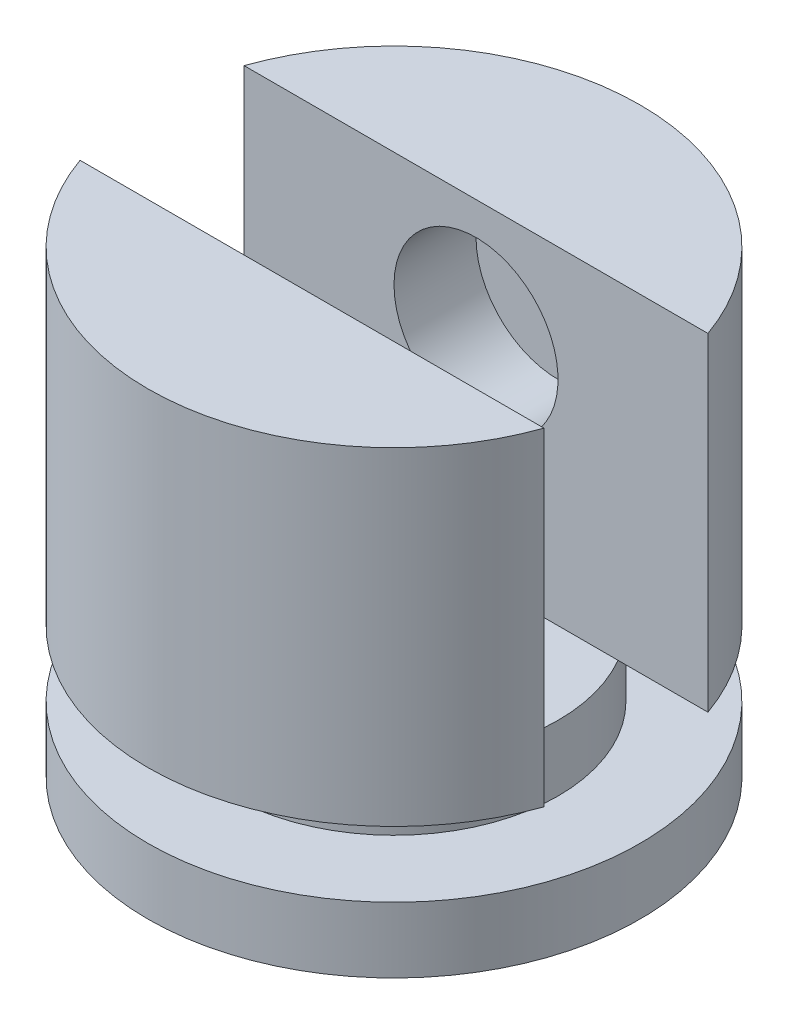
SolidWorks part; units mm, degrees
ref_plane "Front Plane" through (0, 0, 0) normal (0, 0, 1) x (1, 0, 0)
ref_plane "Top Plane" through (0, 0, 0) normal (0, 1, 0) x (1, 0, 0)
ref_plane "Right Plane" through (0, 0, 0) normal (1, 0, 0) x (0, 0, -1)
sketch "Sketch1" plane through (0, 0, 0) normal (0, 1, 0) x (1, 0, 0)
  circle A0 centre (0, 0) radius 10
  dimension "D1" = 20
extrude "Boss-Extrude1" add sketch "Sketch1" against normal blind 4
sketch "Sketch2" plane through (0, -4, 0) normal (0, -1, 0) x (1, 0, 0)
  circle A0 centre (0, 0) radius 15
  dimension "D1" = 30
extrude "Boss-Extrude2" add sketch "Sketch2" along normal blind 4
sketch "Sketch3" plane through (0, 0, 0) normal (0, 1, 0) x (1, 0, 0)
  circle A0 centre (0, 0) radius 15
  dimension "D1" = 30
extrude "Boss-Extrude3" add sketch "Sketch3" along normal blind 20
sketch "Sketch6" plane through (0, 0, 0) normal (0, 1, 0) x (1, 0, 0)
  line L1 (15, 0) -> (-15, 0)
  line L2 (15, 0) -> (15, -5)
  line L3 (15, -5) -> (-15, -5)
  line L4 (-15, 0) -> (-15, -5)
  circle A0 centre (0, 0) radius 15 construction
  dimension "D1" = 30
  dimension "D2" = 5
extrude "Cut-Extrude2" cut sketch "Sketch6" along normal through all
sketch "Sketch7" plane through (0, 0, 5) normal (0, 0, -1) x (-1, 0, 0)
  line L0 (14.1421, 20) -> (-14.1421, 20) construction
  circle A0 centre (0, 13) radius 5
  dimension "D1" = 10
  dimension "D2" = 7
extrude "Cut-Extrude5" cut sketch "Sketch7" against normal blind 5
mirror "Mirror1" about plane through (0, 0, 0) normal (0, 0, 1) of "Cut-Extrude5", "Cut-Extrude2"
